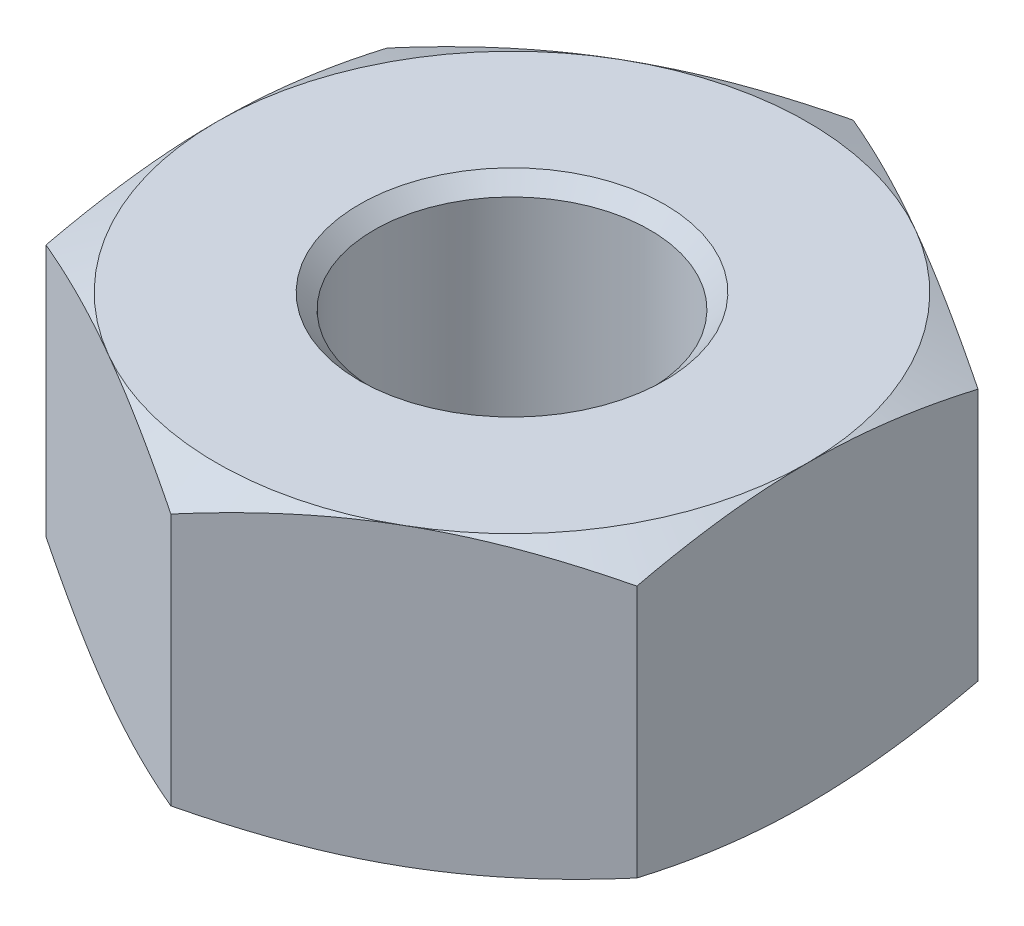
SolidWorks part; units mm, degrees
material "Galvanized Steel"
ref_plane "Front Plane" through (0, 0, 0) normal (0, 0, 1) x (1, 0, 0)
ref_plane "Top Plane" through (0, 0, 0) normal (0, 1, 0) x (1, 0, 0)
ref_plane "Right Plane" through (0, 0, 0) normal (1, 0, 0) x (0, 0, -1)
sketch "Sketch1" plane through (0, 0, 0) normal (0, 1, 0) x (1, 0, 0)
  line L1 (0, 3.4641) -> (-3, 1.7321)
  line L2 (-3, 1.7321) -> (-3, -1.7321)
  line L3 (-3, -1.7321) -> (0, -3.4641)
  line L4 (0, -3.4641) -> (3, -1.7321)
  line L5 (3, -1.7321) -> (3, 1.7321)
  line L6 (3, 1.7321) -> (0, 3.4641)
  circle A0 centre (0, 0) radius 3 construction
  circle A1 centre (0, 0) radius 1.4
  dimension "D2" = 2.8
  dimension "D1" = 6
extrude "Boss-Extrude1" add sketch "Sketch1" along normal mid plane 3
chamfer "Chamfer1" distance 0.15 angle 45 2 edges at (0, -1.5, 1.4) (0, 1.5, 1.4)
sketch "Sketch2" plane through (0, 0, 0) normal (0, 0, 1) x (1, 0, 0)
  line L0 (-3, 1.5) -> (-5, 0.5674)
  line L1 (-5, 0.5674) -> (-5, 1.5)
  line L2 (-5, 1.5) -> (-3, 1.5)
  line L3 (0, 0) -> (0, 3.4047) construction
  dimension "D1" = 5
  dimension "D2" = 25
revolve "Cut-Revolve1" cut sketch "Sketch2" angle 360 about L3
mirror "Mirror1" about plane through (0, 0, 0) normal (0, 1, 0) of "Cut-Revolve1"
